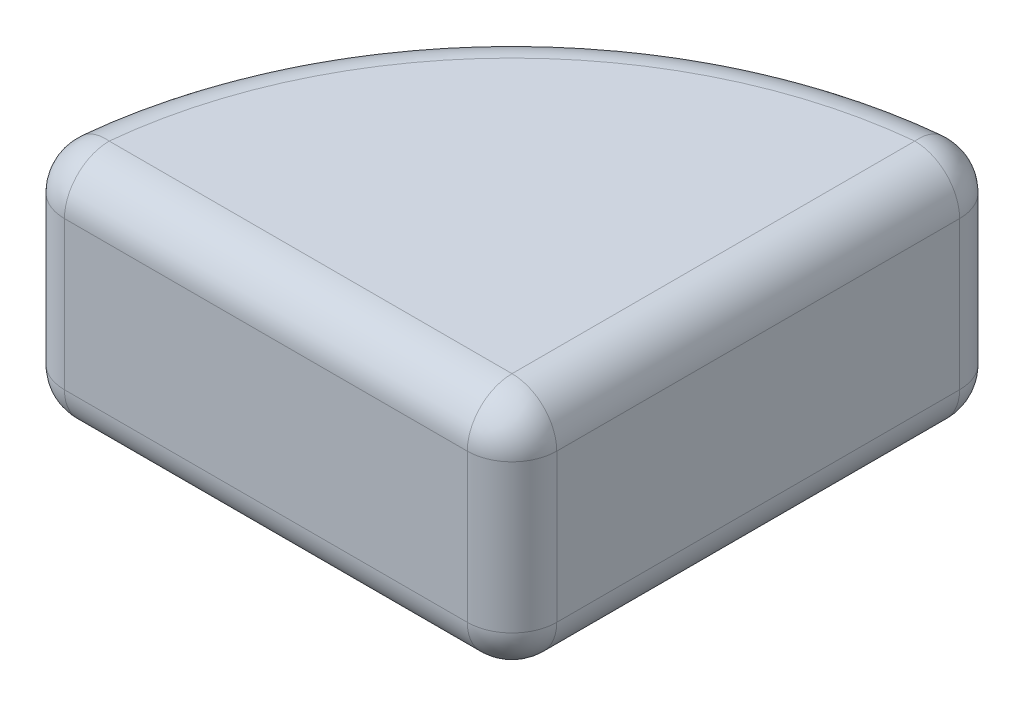
SolidWorks part; units mm, degrees
ref_plane "Front Plane" through (0, 0, 0) normal (0, 0, 1) x (1, 0, 0)
ref_plane "Top Plane" through (0, 0, 0) normal (0, 1, 0) x (1, 0, 0)
ref_plane "Right Plane" through (0, 0, 0) normal (1, 0, 0) x (0, 0, -1)
sketch "Sketch1" plane through (0, 0, 0) normal (0, 1, 0) x (1, 0, 0)
  line L0 (-331.6, 0) -> (0, 0)
  line L1 (0, 0) -> (0, 331.6)
  arc A0 (0, 331.6) -> (-331.6, 0) centre (0, 0) ccw
  dimension "D1" = 331.6
extrude "Boss-Extrude1" add sketch "Sketch1" along normal blind 159.4
fillet "Fillet1" radius 30 9 edges at (-234.4766, 0, -234.4766) (0, 79.7, -331.6) (0, 0, -165.8) (-234.4766, 159.4, -234.4766) (0, 159.4, -165.8) (-331.6, 79.7, 0) (-165.8, 159.4, 0) (0, 79.7, 0) (-165.8, 0, 0)
